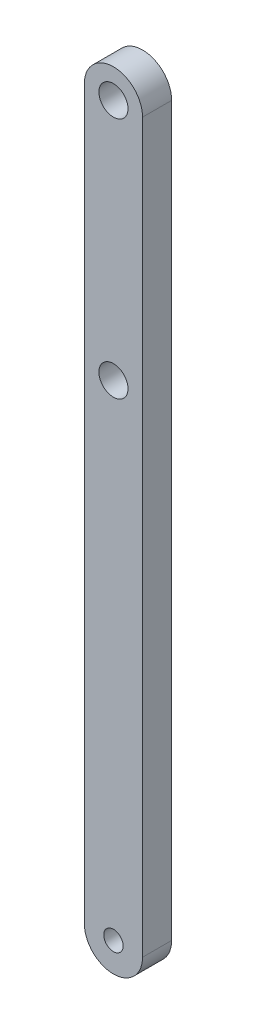
SolidWorks part; units mm, degrees
ref_plane "Front Plane" through (0, 0, 0) normal (0, 0, 1) x (1, 0, 0)
ref_plane "Top Plane" through (0, 0, 0) normal (0, 1, 0) x (1, 0, 0)
ref_plane "Right Plane" through (0, 0, 0) normal (1, 0, 0) x (0, 0, -1)
sketch "Sketch2" plane through (0, 0, 0) normal (0, 0, 1) x (1, 0, 0)
  line L0 (0, 75) -> (0, -75) construction
  line L1 (6, 75) -> (6, -75)
  line L2 (-6, 75) -> (-6, -75)
  arc A0 (6, 75) -> (-6, 75) centre (0, 75) ccw
  arc A1 (-6, -75) -> (6, -75) centre (0, -75) ccw
  circle A2 centre (0, 75) radius 3
  circle A3 centre (0, 25) radius 3
  circle A4 centre (0, -75) radius 2
  point P2 (0, 0)
  dimension "D3" = 6
  dimension "D4" = 6
  dimension "D5" = 6
  dimension "D6" = 4
  dimension "D1" = 150
  dimension "D2" = 50
  dimension "D7" = 100
extrude "Boss-Extrude1" add sketch "Sketch2" against normal blind 6
scale "Scale1" scale about centroid uniform scaling yes scale factor 0.5
